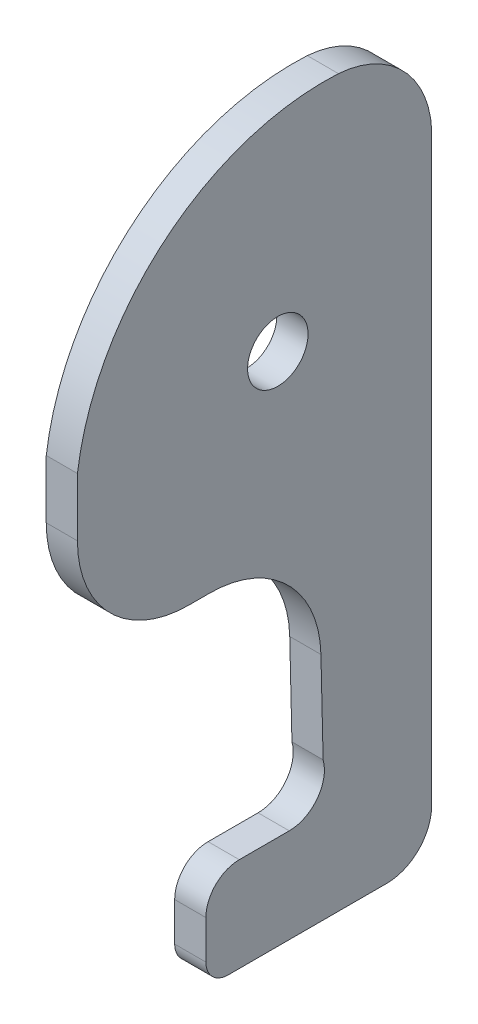
SolidWorks part; units mm, degrees
ref_plane "Front Plane" through (0, 0, 0) normal (0, 0, 1) x (1, 0, 0)
ref_plane "Top Plane" through (0, 0, 0) normal (0, 1, 0) x (1, 0, 0)
ref_plane "Right Plane" through (0, 0, 0) normal (1, 0, 0) x (0, 0, -1)
sketch "Sketch3" plane through (0, 0, 0) normal (1, 0, 0) x (0, 0, -1)
  line L2 (0, -60) -> (0, -86.1848)
  line L3 (50, -136.1848) -> (59.297, -136.1848)
  line L4 (158.939, -50) -> (158.939, -146.1848)
  line L6 (158.939, -146.1848) -> (158.939, -268.7513)
  line L7 (138.939, -288.7513) -> (116.1279, -288.7513)
  line L9 (116.1279, -288.7513) -> (67.6411, -288.7513)
  line L11 (95.0651, -246.4371) -> (72.6411, -246.4371)
  line L12 (57.6411, -278.7513) -> (57.6411, -261.4371)
  line L14 (109.2828, -184.9913) -> (110.2724, -226.4371)
  line L16 (158.939, -11.4803) -> (158.939, -50)
  arc A1 (0, -86.1848) -> (50, -136.1848) centre (50, -86.1848) ccw
  arc A2 (109.2828, -184.9913) -> (59.297, -136.1848) centre (59.297, -186.1848) ccw
  arc A4 (95.0651, -246.4371) -> (110.2724, -226.4371) centre (95.0651, -230.6556) ccw
  arc A5 (57.6411, -261.4371) -> (72.6411, -246.4371) centre (72.6411, -261.4371) cw
  arc A6 (57.6411, -278.7513) -> (67.6411, -288.7513) centre (67.6411, -278.7513) ccw
  arc A7 (158.939, -268.7513) -> (138.939, -288.7513) centre (138.939, -268.7513) cw
  arc A8 (0, -60) -> (117.1561, 36.8308) centre (110.8736, -74.8572) cw
  arc A13 (117.1561, 36.8308) -> (158.939, -11.4803) centre (113.892, -8.2162) cw
  point P13 (0, 0)
  dimension "D1" = 325.5821
  dimension "D2" = 50
  dimension "D3" = 50
  dimension "D6" = 15
  dimension "D7" = 10
  dimension "D8" = 20
extrude "Boss-Extrude1" add sketch "Sketch3" along normal blind 12 and the other way blind 2 contours L9 A6 L12 A5 L11 A4 L14 A2 L3 A1 L2 A8 A13 L16 L4 L6 A7 L7
scale "Scale1" scale about centroid uniform scaling yes scale factor 0.184185
sketch "Sketch4" plane through (6.2893, 0, 0) normal (1, 0, 0) x (0, 0, -1)
  line L0 (107.8543, -87.6192) -> (107.8543, -135.0046) construction
  circle A0 centre (95.1433, -96.0959) radius 2.5
  dimension "D1" = 5
  dimension "D2" = 17.3749
  dimension "D3" = 12.711
extrude "Cut-Extrude1" cut sketch "Sketch4" against normal up to next
